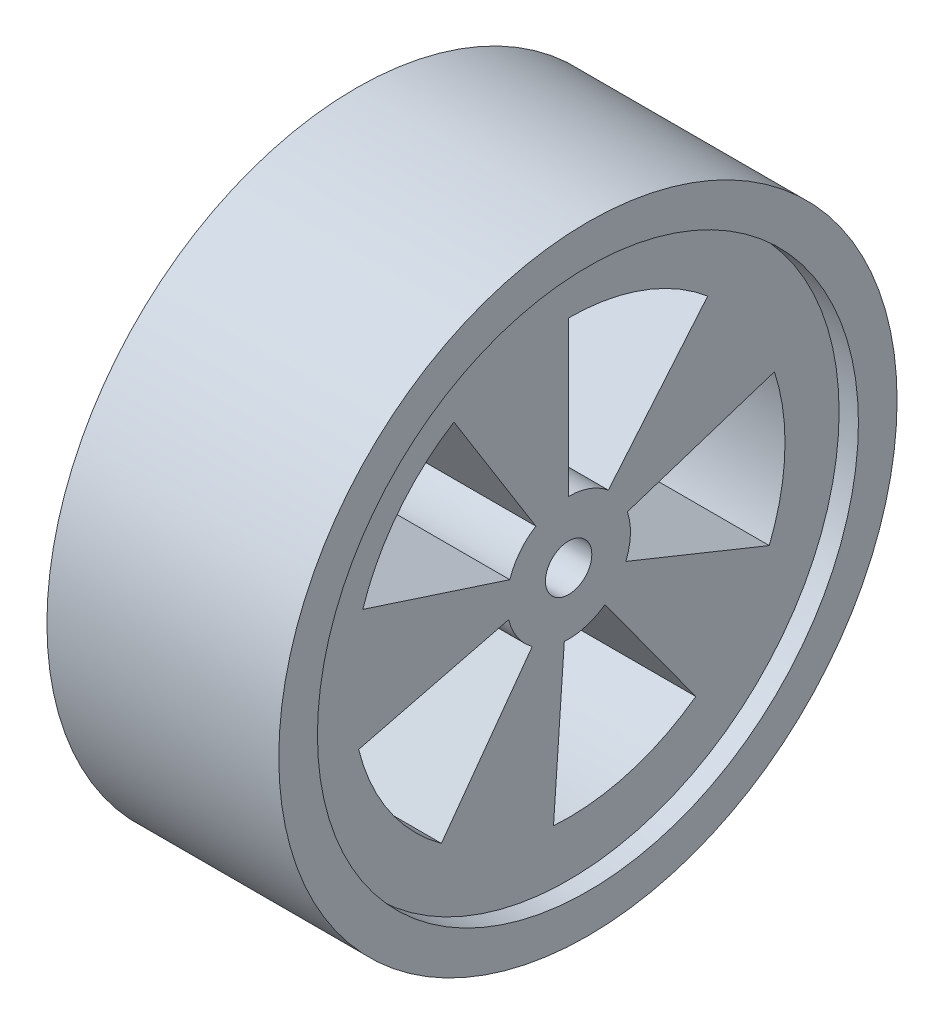
SolidWorks part; units mm, degrees
ref_plane "Front Plane" through (0, 0, 0) normal (0, 0, 1) x (1, 0, 0)
ref_plane "Top Plane" through (0, 0, 0) normal (0, 1, 0) x (1, 0, 0)
ref_plane "Right Plane" through (0, 0, 0) normal (1, 0, 0) x (0, 0, -1)
sketch "Sketch1" plane through (0, 0, 0) normal (1, 0, 0) x (0, 0, -1)
  line L0 (0, 28) -> (0, 8)
  line L1 (5.1423, 6.1284) -> (17.9981, 21.4492)
  line L2 (0, 0) -> (5.1423, 6.1284) construction
  line L3 (26.6296, 8.6525) -> (7.6085, 2.4721)
  line L4 (7.4175, -2.9969) -> (25.9611, -10.489)
  line L5 (16.458, -22.6525) -> (4.7023, -6.4721)
  line L6 (-0.5581, -7.9805) -> (-1.9532, -27.9318)
  line L7 (-16.458, -22.6525) -> (-4.7023, -6.4721)
  line L8 (-7.7624, -1.9354) -> (-27.1683, -6.7738)
  line L9 (-26.6296, 8.6525) -> (-7.6085, 2.4721)
  line L10 (-4.2394, 6.7844) -> (-14.8377, 23.7453)
  circle A0 centre (0, 0) radius 35
  circle A1 centre (0, 0) radius 3
  arc A2 (5.1423, 6.1284) -> (0, 8) centre (0, 0) ccw
  arc A3 (17.9981, 21.4492) -> (0, 28) centre (0, 0) ccw
  arc A4 (25.9611, -10.489) -> (26.6296, 8.6525) centre (0, 0) ccw
  arc A5 (7.4175, -2.9969) -> (7.6085, 2.4721) centre (0, 0) ccw
  arc A6 (-1.9532, -27.9318) -> (16.458, -22.6525) centre (0, 0) ccw
  arc A7 (-0.5581, -7.9805) -> (4.7023, -6.4721) centre (0, 0) ccw
  arc A8 (-27.1683, -6.7738) -> (-16.458, -22.6525) centre (0, 0) ccw
  arc A9 (-7.7624, -1.9354) -> (-4.7023, -6.4721) centre (0, 0) ccw
  arc A10 (-14.8377, 23.7453) -> (-26.6296, 8.6525) centre (0, 0) ccw
  arc A11 (-4.2394, 6.7844) -> (-7.6085, 2.4721) centre (0, 0) ccw
  point P26 (0, 0)
  dimension "D1" = 6
  dimension "D2" = 70
  dimension "D4" = 8
  dimension "D5" = 28
  dimension "D3" = 40
  dimension "D6" = 5
extrude "Boss-Extrude1" add sketch "Sketch1" along normal mid plane 25
sketch "Sketch2" plane through (0, 0, 0) normal (1, 0, 0) x (0, 0, -1)
  circle A0 centre (0, 0) radius 35 construction
  circle A1 centre (0, 0) radius 35
  circle A2 centre (0, 0) radius 40
  dimension "D1" = 80
extrude "Boss-Extrude2" add sketch "Sketch2" along normal mid plane 30
